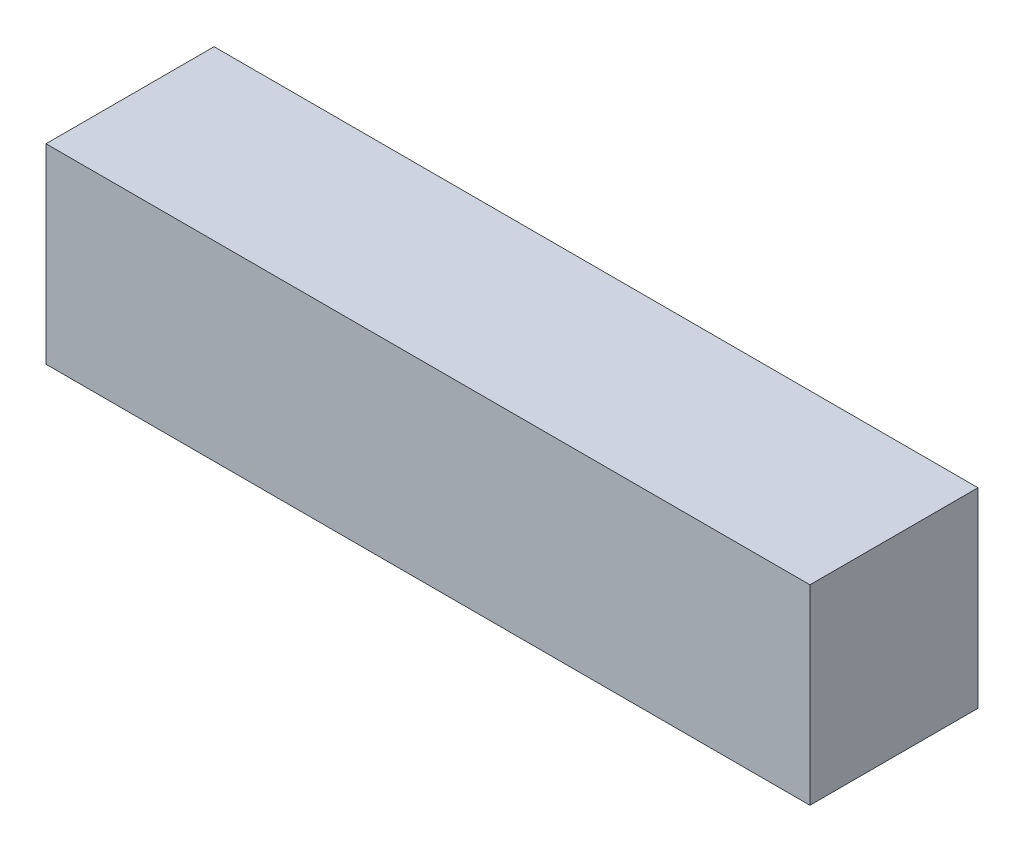
SolidWorks part; units mm, degrees
ref_plane "Front Plane" through (0, 0, 0) normal (0, 0, 1) x (1, 0, 0)
ref_plane "Top Plane" through (0, 0, 0) normal (0, 1, 0) x (1, 0, 0)
ref_plane "Right Plane" through (0, 0, 0) normal (1, 0, 0) x (0, 0, -1)
sketch "Sketch1" plane through (0, 0, 0) normal (0, 0, 1) x (1, 0, 0)
  line L1 (0, 0) -> (12.7, 0)
  line L2 (0, 0) -> (0, 3.175)
  line L3 (0, 3.175) -> (12.7, 3.175)
  line L4 (12.7, 0) -> (12.7, 3.175)
  dimension "D1" = 12.7
  dimension "D2" = 3.175
extrude "Boss-Extrude1" add sketch "Sketch1" along normal blind 2.794
